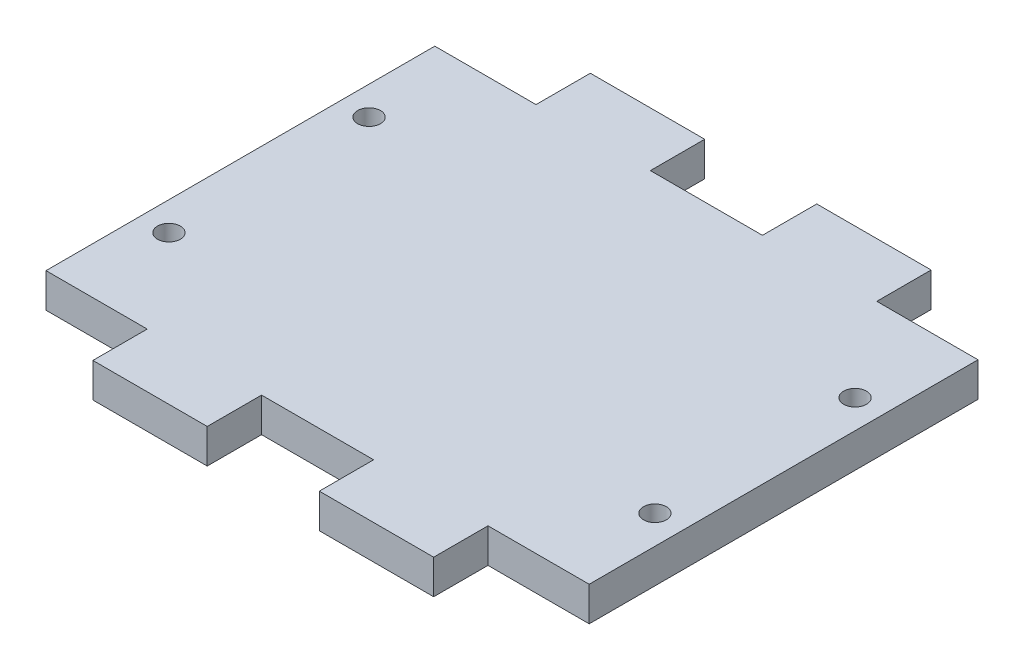
SolidWorks part; units mm, degrees
ref_plane "Front Plane" through (0, 0, 0) normal (0, 0, 1) x (1, 0, 0)
ref_plane "Top Plane" through (0, 0, 0) normal (0, 1, 0) x (1, 0, 0)
ref_plane "Right Plane" through (0, 0, 0) normal (1, 0, 0) x (0, 0, -1)
sketch "Sketch1" plane through (0, 0, 0) normal (0, 1, 0) x (1, 0, 0)
  line L0 (-23.75, -17) -> (-14.9, -17)
  line L1 (23.75, -17) -> (14.9, -17)
  line L2 (23.75, -17) -> (23.75, 17)
  line L3 (23.75, 17) -> (14.9, 17)
  line L4 (-23.75, -17) -> (-23.75, 17)
  line L5 (23.75, -17) -> (-23.75, 17) construction
  line L6 (23.75, 17) -> (-23.75, -17) construction
  line L7 (23.75, -17) -> (14.9, -17)
  line L8 (-14.9, -17) -> (-23.75, -17)
  line L10 (-4.9, -17) -> (4.9, -17)
  line L11 (-14.9, 17) -> (-23.75, 17)
  line L13 (-14.9, -17) -> (-14.9, -21.75)
  line L14 (-14.9, -21.75) -> (-4.9, -21.75)
  line L15 (-4.9, -17) -> (-4.9, -21.75)
  line L17 (4.9, -17) -> (4.9, -21.75)
  line L18 (4.9, -21.75) -> (14.9, -21.75)
  line L19 (14.9, -17) -> (14.9, -21.75)
  line L21 (-14.9, 17) -> (-14.9, 21.75)
  line L22 (-14.9, 21.75) -> (-4.9, 21.75)
  line L23 (-4.9, 17) -> (-4.9, 21.75)
  line L25 (4.9, 17) -> (4.9, 21.75)
  line L26 (4.9, 21.75) -> (14.9, 21.75)
  line L27 (14.9, 17) -> (14.9, 21.75)
  line L28 (4.9, 17) -> (-4.9, 17)
  line L29 (4.9, -17) -> (-4.9, -17)
  point P0 (0, 0)
  dimension "D1" = 47.5
  dimension "D2" = 34
  dimension "D3" = 9.8
  dimension "D5" = 10
  dimension "D6" = 10
  dimension "D8" = 4.75
extrude "Boss-Extrude1" add sketch "Sketch1" along normal blind 3 contours L25 L28 L23 L22 L21 L11 L4 L0 L13 L14 L15 L10 L17 L18 L19 L1 L2 L3 L27 L26
sketch "Sketch2" plane through (0, 3, 0) normal (0, 1, 0) x (1, 0, 0)
  line L0 (-21.25, 8.75) -> (-21.25, -8.75) construction
  line L1 (-21.25, -8.75) -> (21.25, -8.75) construction
  line L2 (21.25, -8.75) -> (21.25, 8.75) construction
  line L3 (21.25, 8.75) -> (-21.25, 8.75) construction
  line L4 (-21.25, 0) -> (-23.75, 0) construction
  line L5 (-23.75, -17) -> (-23.75, 17) construction
  line L6 (21.25, 0) -> (23.75, 0) construction
  line L7 (23.75, -17) -> (23.75, 17) construction
  line L8 (0, 8.75) -> (0, 17) construction
  line L9 (4.9, 17) -> (-4.9, 17) construction
  line L10 (0, -8.75) -> (0, -17) construction
  line L11 (-4.9, -17) -> (4.9, -17) construction
  circle A0 centre (-21.25, 8.75) radius 1
  circle A4 centre (-21.25, -8.75) radius 1
  circle A5 centre (21.25, -8.75) radius 1
  circle A6 centre (21.25, 8.75) radius 1
  dimension "D3" = 2
  dimension "D1" = 42.5
  dimension "D2" = 17.5
extrude "Cut-Extrude1" cut sketch "Sketch2" against normal blind 10
